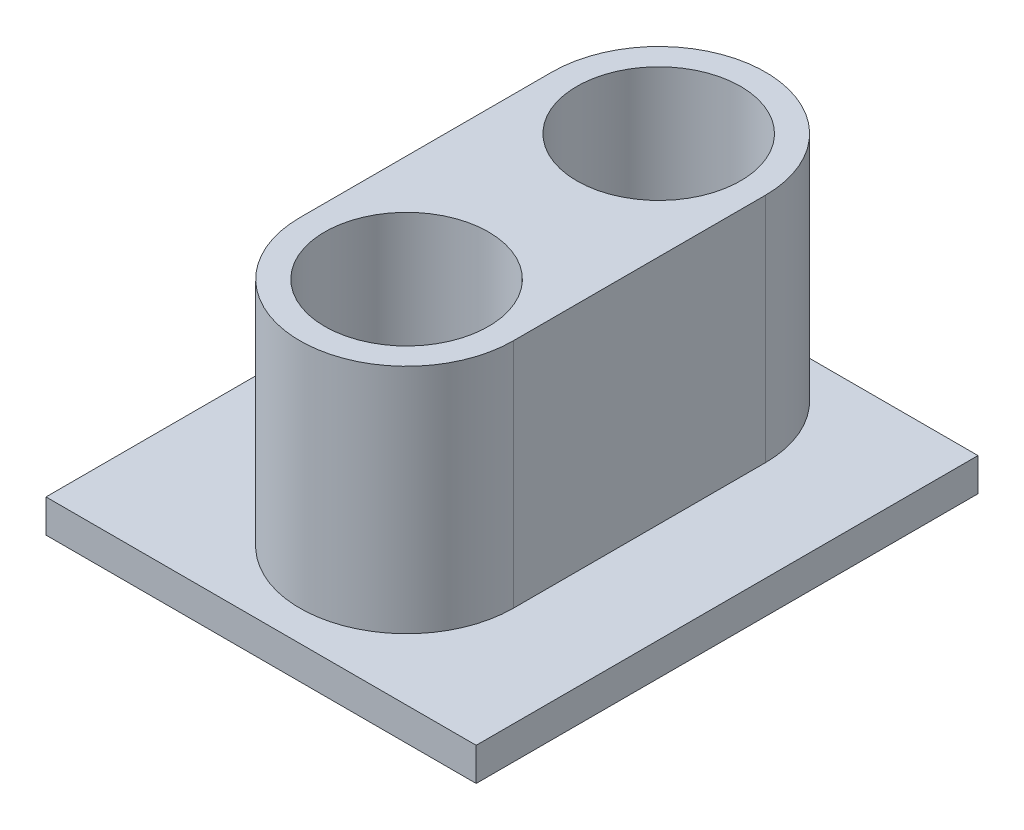
SolidWorks part; units mm, degrees
material "ABS"
ref_plane "Спереди" through (0, 0, 0) normal (0, 0, 1) x (1, 0, 0)
ref_plane "Сверху" through (0, 0, 0) normal (0, 1, 0) x (1, 0, 0)
ref_plane "Справа" through (0, 0, 0) normal (1, 0, 0) x (0, 0, -1)
sketch "Эскиз1" plane through (0, 0, 0) normal (0, 1, 0) x (1, 0, 0)
  line L0 (-13, -15.165) -> (13, -15.165)
  line L1 (-13, -15.165) -> (-13, 15.165)
  line L2 (-13, 15.165) -> (13, 15.165)
  line L3 (13, -15.165) -> (13, 15.165)
extrude "Бобышка-Вытянуть1" add sketch "Эскиз1" along normal blind 2
sketch "Эскиз2" plane through (0, 2, 0) normal (0, 1, 0) x (1, 0, 0)
  circle A2 centre (0.5, -6.87) radius 4.95
  circle A3 centre (0.5, 8.367) radius 4.95
extrude "Вырез-Вытянуть1" cut sketch "Эскиз2" against normal through all
sketch "Эскиз3" plane through (0, 2, 0) normal (0, 1, 0) x (1, 0, 0)
  line L0 (-5.95, -6.87) -> (-5.95, 8.367)
  line L1 (6.95, -6.87) -> (6.95, 8.367)
  circle A0 centre (0.5, -6.87) radius 4.95
  circle A1 centre (0.5, 8.367) radius 4.95
  arc A2 (6.95, 8.367) -> (-5.95, 8.367) centre (0.5, 8.367) ccw
  arc A3 (-5.95, -6.87) -> (6.95, -6.87) centre (0.5, -6.87) ccw
  circle A4 centre (0.5, 8.367) radius 6.45 construction
  circle A5 centre (0.5, -6.87) radius 6.45 construction
  dimension "D1" = 1.5
extrude "Бобышка-Вытянуть2" add sketch "Эскиз3" along normal blind 14
